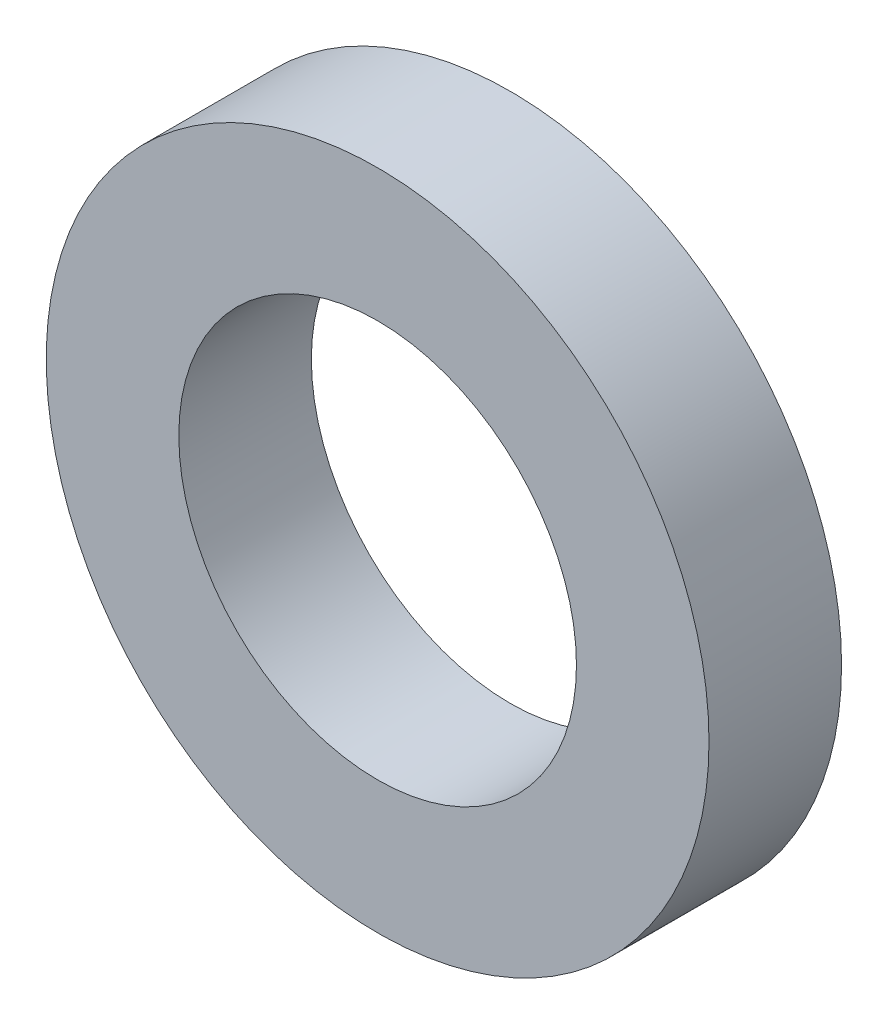
SolidWorks part; units mm, degrees
ref_plane "Спереди" through (0, 0, 0) normal (0, 0, 1) x (1, 0, 0)
ref_plane "Сверху" through (0, 0, 0) normal (0, 1, 0) x (1, 0, 0)
ref_plane "Справа" through (0, 0, 0) normal (1, 0, 0) x (0, 0, -1)
sketch "Эскиз1" plane through (0, 0, 0) normal (0, 0, 1) x (1, 0, 0)
  circle A0 centre (0, 0) radius 15
  circle A1 centre (0, 0) radius 25
extrude "Вытянуть1" add sketch "Эскиз1" along normal blind 10
